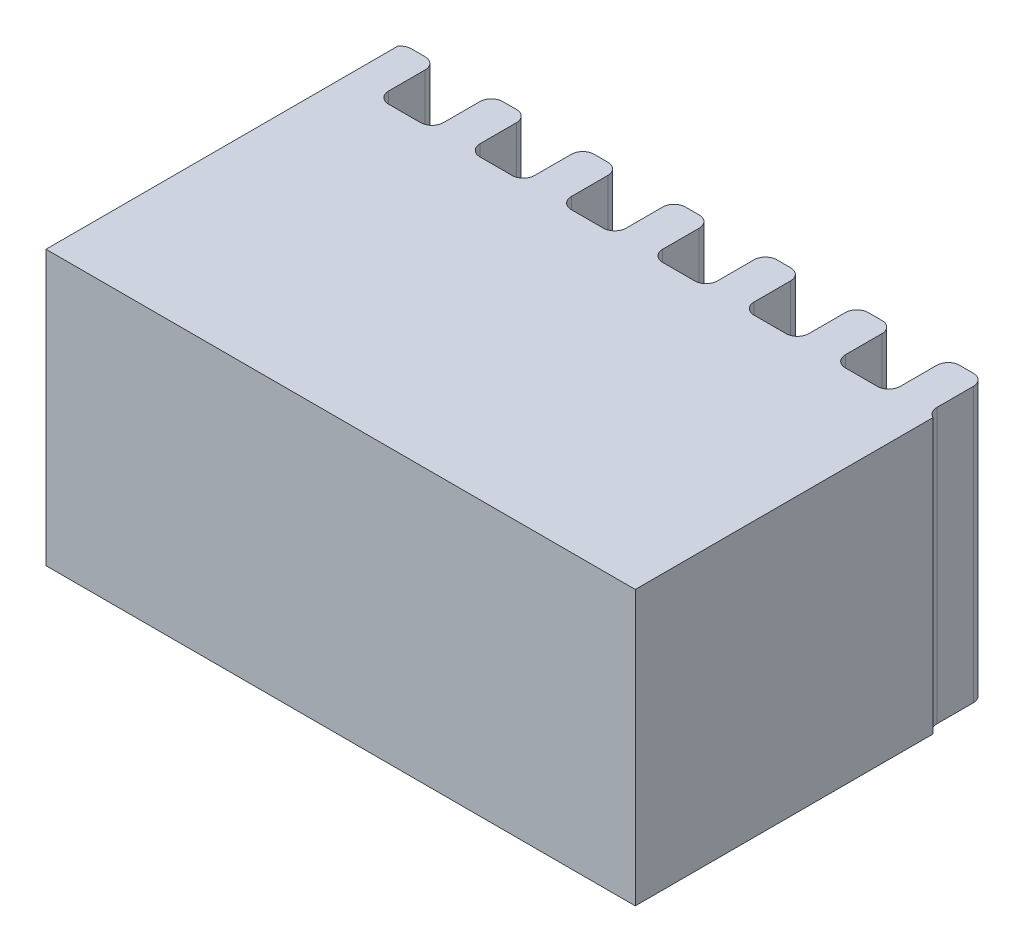
SolidWorks part; units mm, degrees
ref_plane "前视基准面" through (0, 0, 0) normal (0, 0, 1) x (1, 0, 0)
ref_plane "上视基准面" through (0, 0, 0) normal (0, 1, 0) x (1, 0, 0)
ref_plane "右视基准面" through (0, 0, 0) normal (1, 0, 0) x (0, 0, -1)
sketch "草图1" plane through (0, 0, 0) normal (0, 1, 0) x (1, 0, 0)
  line L1 (0, 0) -> (45, 0)
  line L2 (0, 0) -> (0, 26)
  line L3 (0, 26) -> (45, 26)
  line L4 (45, 0) -> (45, 26)
  dimension "D1" = 26
  dimension "D2" = 45
extrude "凸台-拉伸1" add sketch "草图1" along normal blind 10
sketch "草图3" plane through (0, 10, 0) normal (0, 1, 0) x (1, 0, 0)
  line L1 (44.35, 9.3) -> (44.35, 7.2991) construction
  line L3 (43, 8) -> (43.7, 8)
  line L4 (44.75, 8.25) -> (44.75, 9.05)
  line L5 (44.5, 9.3) -> (44.2, 9.3)
  line L6 (45, 0) -> (45, 26) construction
  line L7 (43.95, 8.25) -> (43.95, 9.05)
  line L8 (41, 8) -> (41.7, 8)
  line L9 (41.95, 8.25) -> (41.95, 9.05)
  line L10 (42.5, 9.3) -> (42.2, 9.3)
  line L11 (42.75, 8.25) -> (42.75, 9.05)
  line L12 (39, 8) -> (39.7, 8)
  line L13 (39.95, 8.25) -> (39.95, 9.05)
  line L14 (40.5, 9.3) -> (40.2, 9.3)
  line L15 (40.75, 8.25) -> (40.75, 9.05)
  line L16 (37, 8) -> (37.7, 8)
  line L17 (37.95, 8.25) -> (37.95, 9.05)
  line L18 (38.5, 9.3) -> (38.2, 9.3)
  line L19 (38.75, 8.25) -> (38.75, 9.05)
  line L20 (35, 8) -> (35.7, 8)
  line L21 (35.95, 8.25) -> (35.95, 9.05)
  line L22 (36.5, 9.3) -> (36.2, 9.3)
  line L23 (36.75, 8.25) -> (36.75, 9.05)
  line L24 (33, 8) -> (33.7, 8)
  line L25 (33.95, 8.25) -> (33.95, 9.05)
  line L26 (34.5, 9.3) -> (34.2, 9.3)
  line L27 (34.75, 8.25) -> (34.75, 9.05)
  line L28 (31, 8) -> (31.7, 8)
  line L29 (31.95, 8.25) -> (31.95, 9.05)
  line L30 (32.5, 9.3) -> (32.2, 9.3)
  line L31 (32.75, 8.25) -> (32.75, 9.05)
  line L32 (29, 8) -> (29.7, 8)
  line L33 (29.95, 8.25) -> (29.95, 9.05)
  line L34 (30.5, 9.3) -> (30.2, 9.3)
  line L35 (30.75, 8.25) -> (30.75, 9.05)
  line L36 (27, 8) -> (27.7, 8)
  line L37 (27.95, 8.25) -> (27.95, 9.05)
  line L38 (28.5, 9.3) -> (28.2, 9.3)
  line L39 (28.75, 8.25) -> (28.75, 9.05)
  line L40 (25, 8) -> (25.7, 8)
  line L41 (25.95, 8.25) -> (25.95, 9.05)
  line L42 (26.5, 9.3) -> (26.2, 9.3)
  line L43 (26.75, 8.25) -> (26.75, 9.05)
  line L44 (23, 8) -> (23.7, 8)
  line L45 (23.95, 8.25) -> (23.95, 9.05)
  line L46 (24.5, 9.3) -> (24.2, 9.3)
  line L47 (24.75, 8.25) -> (24.75, 9.05)
  line L48 (21, 8) -> (21.7, 8)
  line L49 (21.95, 8.25) -> (21.95, 9.05)
  line L50 (22.5, 9.3) -> (22.2, 9.3)
  line L51 (22.75, 8.25) -> (22.75, 9.05)
  line L52 (19, 8) -> (19.7, 8)
  line L53 (19.95, 8.25) -> (19.95, 9.05)
  line L54 (20.5, 9.3) -> (20.2, 9.3)
  line L55 (20.75, 8.25) -> (20.75, 9.05)
  line L56 (17, 8) -> (17.7, 8)
  line L57 (17.95, 8.25) -> (17.95, 9.05)
  line L58 (18.5, 9.3) -> (18.2, 9.3)
  line L59 (18.75, 8.25) -> (18.75, 9.05)
  line L60 (15, 8) -> (15.7, 8)
  line L61 (15.95, 8.25) -> (15.95, 9.05)
  line L62 (16.5, 9.3) -> (16.2, 9.3)
  line L63 (16.75, 8.25) -> (16.75, 9.05)
  line L64 (13, 8) -> (13.7, 8)
  line L65 (13.95, 8.25) -> (13.95, 9.05)
  line L66 (14.5, 9.3) -> (14.2, 9.3)
  line L67 (14.75, 8.25) -> (14.75, 9.05)
  line L68 (11, 8) -> (11.7, 8)
  line L69 (11.95, 8.25) -> (11.95, 9.05)
  line L70 (12.5, 9.3) -> (12.2, 9.3)
  line L71 (12.75, 8.25) -> (12.75, 9.05)
  line L72 (9, 8) -> (9.7, 8)
  line L73 (9.95, 8.25) -> (9.95, 9.05)
  line L74 (10.5, 9.3) -> (10.2, 9.3)
  line L75 (10.75, 8.25) -> (10.75, 9.05)
  line L76 (7, 8) -> (7.7, 8)
  line L77 (7.95, 8.25) -> (7.95, 9.05)
  line L78 (8.5, 9.3) -> (8.2, 9.3)
  line L79 (8.75, 8.25) -> (8.75, 9.05)
  line L80 (5, 8) -> (5.7, 8)
  line L81 (5.95, 8.25) -> (5.95, 9.05)
  line L82 (6.5, 9.3) -> (6.2, 9.3)
  line L83 (6.75, 8.25) -> (6.75, 9.05)
  line L84 (3, 8) -> (3.7, 8)
  line L85 (3.95, 8.25) -> (3.95, 9.05)
  line L86 (4.5, 9.3) -> (4.2, 9.3)
  line L87 (4.75, 8.25) -> (4.75, 9.05)
  line L88 (1, 8) -> (1.7, 8)
  line L89 (1.95, 8.25) -> (1.95, 9.05)
  line L90 (2.5, 9.3) -> (2.2, 9.3)
  line L91 (2.75, 8.25) -> (2.75, 9.05)
  line L92 (0, 10.2) -> (0, 9.2)
  line L94 (0.5, 9.3) -> (0.2, 9.3)
  line L95 (0.75, 8.25) -> (0.75, 9.05)
  line L96 (0, 10.2) -> (45, 10.2)
  line L97 (0, 26) -> (0, 0) construction
  line L98 (45, 8) -> (45, 10.2)
  line L101 (-0.05, 8.25) -> (-0.05, 9.05) [skipped]
  line L102 (-1, 8) -> (-0.3, 8) [skipped]
  arc A0 (45, 8) -> (44.75, 8.25) centre (45, 8.25) cw
  arc A1 (44.75, 9.05) -> (44.5, 9.3) centre (44.5, 9.05) ccw
  arc A2 (43.7, 8) -> (43.95, 8.25) centre (43.7, 8.25) ccw
  arc A3 (43.95, 9.05) -> (44.2, 9.3) centre (44.2, 9.05) cw
  arc A4 (41.7, 8) -> (41.95, 8.25) centre (41.7, 8.25) ccw
  arc A5 (41.95, 9.05) -> (42.2, 9.3) centre (42.2, 9.05) cw
  arc A6 (42.75, 9.05) -> (42.5, 9.3) centre (42.5, 9.05) ccw
  arc A7 (43, 8) -> (42.75, 8.25) centre (43, 8.25) cw
  arc A8 (39.7, 8) -> (39.95, 8.25) centre (39.7, 8.25) ccw
  arc A9 (39.95, 9.05) -> (40.2, 9.3) centre (40.2, 9.05) cw
  arc A10 (40.75, 9.05) -> (40.5, 9.3) centre (40.5, 9.05) ccw
  arc A11 (41, 8) -> (40.75, 8.25) centre (41, 8.25) cw
  arc A12 (37.7, 8) -> (37.95, 8.25) centre (37.7, 8.25) ccw
  arc A13 (37.95, 9.05) -> (38.2, 9.3) centre (38.2, 9.05) cw
  arc A14 (38.75, 9.05) -> (38.5, 9.3) centre (38.5, 9.05) ccw
  arc A15 (39, 8) -> (38.75, 8.25) centre (39, 8.25) cw
  arc A16 (35.7, 8) -> (35.95, 8.25) centre (35.7, 8.25) ccw
  arc A17 (35.95, 9.05) -> (36.2, 9.3) centre (36.2, 9.05) cw
  arc A18 (36.75, 9.05) -> (36.5, 9.3) centre (36.5, 9.05) ccw
  arc A19 (37, 8) -> (36.75, 8.25) centre (37, 8.25) cw
  arc A20 (33.7, 8) -> (33.95, 8.25) centre (33.7, 8.25) ccw
  arc A21 (33.95, 9.05) -> (34.2, 9.3) centre (34.2, 9.05) cw
  arc A22 (34.75, 9.05) -> (34.5, 9.3) centre (34.5, 9.05) ccw
  arc A23 (35, 8) -> (34.75, 8.25) centre (35, 8.25) cw
  arc A24 (31.7, 8) -> (31.95, 8.25) centre (31.7, 8.25) ccw
  arc A25 (31.95, 9.05) -> (32.2, 9.3) centre (32.2, 9.05) cw
  arc A26 (32.75, 9.05) -> (32.5, 9.3) centre (32.5, 9.05) ccw
  arc A27 (33, 8) -> (32.75, 8.25) centre (33, 8.25) cw
  arc A28 (29.7, 8) -> (29.95, 8.25) centre (29.7, 8.25) ccw
  arc A29 (29.95, 9.05) -> (30.2, 9.3) centre (30.2, 9.05) cw
  arc A30 (30.75, 9.05) -> (30.5, 9.3) centre (30.5, 9.05) ccw
  arc A31 (31, 8) -> (30.75, 8.25) centre (31, 8.25) cw
  arc A32 (27.7, 8) -> (27.95, 8.25) centre (27.7, 8.25) ccw
  arc A33 (27.95, 9.05) -> (28.2, 9.3) centre (28.2, 9.05) cw
  arc A34 (28.75, 9.05) -> (28.5, 9.3) centre (28.5, 9.05) ccw
  arc A35 (29, 8) -> (28.75, 8.25) centre (29, 8.25) cw
  arc A36 (25.7, 8) -> (25.95, 8.25) centre (25.7, 8.25) ccw
  arc A37 (25.95, 9.05) -> (26.2, 9.3) centre (26.2, 9.05) cw
  arc A38 (26.75, 9.05) -> (26.5, 9.3) centre (26.5, 9.05) ccw
  arc A39 (27, 8) -> (26.75, 8.25) centre (27, 8.25) cw
  arc A40 (23.7, 8) -> (23.95, 8.25) centre (23.7, 8.25) ccw
  arc A41 (23.95, 9.05) -> (24.2, 9.3) centre (24.2, 9.05) cw
  arc A42 (24.75, 9.05) -> (24.5, 9.3) centre (24.5, 9.05) ccw
  arc A43 (25, 8) -> (24.75, 8.25) centre (25, 8.25) cw
  arc A44 (21.7, 8) -> (21.95, 8.25) centre (21.7, 8.25) ccw
  arc A45 (21.95, 9.05) -> (22.2, 9.3) centre (22.2, 9.05) cw
  arc A46 (22.75, 9.05) -> (22.5, 9.3) centre (22.5, 9.05) ccw
  arc A47 (23, 8) -> (22.75, 8.25) centre (23, 8.25) cw
  arc A48 (19.7, 8) -> (19.95, 8.25) centre (19.7, 8.25) ccw
  arc A49 (19.95, 9.05) -> (20.2, 9.3) centre (20.2, 9.05) cw
  arc A50 (20.75, 9.05) -> (20.5, 9.3) centre (20.5, 9.05) ccw
  arc A51 (21, 8) -> (20.75, 8.25) centre (21, 8.25) cw
  arc A52 (17.7, 8) -> (17.95, 8.25) centre (17.7, 8.25) ccw
  arc A53 (17.95, 9.05) -> (18.2, 9.3) centre (18.2, 9.05) cw
  arc A54 (18.75, 9.05) -> (18.5, 9.3) centre (18.5, 9.05) ccw
  arc A55 (19, 8) -> (18.75, 8.25) centre (19, 8.25) cw
  arc A56 (15.7, 8) -> (15.95, 8.25) centre (15.7, 8.25) ccw
  arc A57 (15.95, 9.05) -> (16.2, 9.3) centre (16.2, 9.05) cw
  arc A58 (16.75, 9.05) -> (16.5, 9.3) centre (16.5, 9.05) ccw
  arc A59 (17, 8) -> (16.75, 8.25) centre (17, 8.25) cw
  arc A60 (13.7, 8) -> (13.95, 8.25) centre (13.7, 8.25) ccw
  arc A61 (13.95, 9.05) -> (14.2, 9.3) centre (14.2, 9.05) cw
  arc A62 (14.75, 9.05) -> (14.5, 9.3) centre (14.5, 9.05) ccw
  arc A63 (15, 8) -> (14.75, 8.25) centre (15, 8.25) cw
  arc A64 (11.7, 8) -> (11.95, 8.25) centre (11.7, 8.25) ccw
  arc A65 (11.95, 9.05) -> (12.2, 9.3) centre (12.2, 9.05) cw
  arc A66 (12.75, 9.05) -> (12.5, 9.3) centre (12.5, 9.05) ccw
  arc A67 (13, 8) -> (12.75, 8.25) centre (13, 8.25) cw
  arc A68 (9.7, 8) -> (9.95, 8.25) centre (9.7, 8.25) ccw
  arc A69 (9.95, 9.05) -> (10.2, 9.3) centre (10.2, 9.05) cw
  arc A70 (10.75, 9.05) -> (10.5, 9.3) centre (10.5, 9.05) ccw
  arc A71 (11, 8) -> (10.75, 8.25) centre (11, 8.25) cw
  arc A72 (7.7, 8) -> (7.95, 8.25) centre (7.7, 8.25) ccw
  arc A73 (7.95, 9.05) -> (8.2, 9.3) centre (8.2, 9.05) cw
  arc A74 (8.75, 9.05) -> (8.5, 9.3) centre (8.5, 9.05) ccw
  arc A75 (9, 8) -> (8.75, 8.25) centre (9, 8.25) cw
  arc A76 (5.7, 8) -> (5.95, 8.25) centre (5.7, 8.25) ccw
  arc A77 (5.95, 9.05) -> (6.2, 9.3) centre (6.2, 9.05) cw
  arc A78 (6.75, 9.05) -> (6.5, 9.3) centre (6.5, 9.05) ccw
  arc A79 (7, 8) -> (6.75, 8.25) centre (7, 8.25) cw
  arc A80 (3.7, 8) -> (3.95, 8.25) centre (3.7, 8.25) ccw
  arc A81 (3.95, 9.05) -> (4.2, 9.3) centre (4.2, 9.05) cw
  arc A82 (4.75, 9.05) -> (4.5, 9.3) centre (4.5, 9.05) ccw
  arc A83 (5, 8) -> (4.75, 8.25) centre (5, 8.25) cw
  arc A84 (1.7, 8) -> (1.95, 8.25) centre (1.7, 8.25) ccw
  arc A85 (1.95, 9.05) -> (2.2, 9.3) centre (2.2, 9.05) cw
  arc A86 (2.75, 9.05) -> (2.5, 9.3) centre (2.5, 9.05) ccw
  arc A87 (3, 8) -> (2.75, 8.25) centre (3, 8.25) cw
  arc A89 (0, 9.2) -> (0.2, 9.3) centre (0.2, 9.05) cw
  arc A90 (0.75, 9.05) -> (0.5, 9.3) centre (0.5, 9.05) ccw
  arc A91 (1, 8) -> (0.75, 8.25) centre (1, 8.25) cw
  arc A92 (-0.3, 8) -> (-0.05, 8.25) centre (-0.3, 8.25) ccw [skipped]
  dimension "D2" = 2
  dimension "D4" = 0.25
  dimension "D5" = 0.25
  dimension "D1" = 0
  dimension "D3" = 23
  dimension "D6" = 0.8
  dimension "D7" = 0.9
extrude "切除-拉伸1" cut sketch "草图3" against normal blind 6
sketch "草图4" plane through (0, 10, 0) normal (0, 1, 0) x (1, 0, 0)
  line L1 (45, 8) -> (15, 8)
  line L2 (45, 8) -> (45, 9.4)
  line L3 (45, 9.4) -> (15, 9.4)
  line L4 (15, 8) -> (15, 9.4)
  dimension "D1" = 1.4
  dimension "D2" = 30
extrude "切除-拉伸3" cut sketch "草图4" against normal blind 6
sketch "草图5" plane through (45, 0, 0) normal (1, 0, 0) x (0, 0, -1)
  line L0 (8, 7) -> (0, 7) construction
  line L1 (8, 4) -> (8, 10) construction
  line L2 (0, 10) -> (0, 0) construction
  line L3 (4.5, 10) -> (4.5, 0) construction
  line L4 (0, 10) -> (8, 10) construction
  line L5 (0, 0) -> (26, 0) construction
  circle A0 centre (4.5, 7) radius 1.8
  dimension "D3" = 3.6
  dimension "D1" = 3
  dimension "D2" = 3.5
extrude "切除-拉伸4" cut sketch "草图5" against normal blind 30
sketch "草图6" plane through (0, 10, 0) normal (0, 1, 0) x (1, 0, 0)
  line L0 (45, 4.5) -> (25.0035, 4.5) construction
  line L1 (45, 0) -> (45, 8) construction
  line L2 (15, 8) -> (45, 8) construction
  line L4 (37.2, 7.5) -> (40, 7.5)
  line L5 (37.2, 7.5) -> (37.2, 1.5)
  line L6 (37.2, 1.5) -> (40, 1.5)
  line L7 (40, 7.5) -> (40, 1.5)
  dimension "D1" = 3.5
  dimension "D2" = 5
  dimension "D3" = 2.8
  dimension "D4" = 6
  dimension "D5" = 3
extrude "切除-拉伸5" cut sketch "草图6" against normal blind 6.5
sketch "草图7" plane through (0, 10, 0) normal (0, 1, 0) x (1, 0, 0)
  line L0 (37.2, 7.5) -> (37.2, 1.5) construction
  line L1 (35.2, 1.5) -> (12.9, 1.5)
  line L2 (35.2, 1.5) -> (35.2, 9.613)
  line L3 (35.2, 9.613) -> (12.9, 9.613)
  line L4 (12.9, 1.5) -> (12.9, 9.613)
  line L5 (0, 0) -> (45, 0) construction
  dimension "D1" = 2
  dimension "D2" = 22.3
  dimension "D3" = 1.5
extrude "切除-拉伸7" cut sketch "草图7" against normal blind 6
sketch "草图8" plane through (0, 0, -26) normal (0, 0, -1) x (-1, 0, 0)
  line L0 (0, 5) -> (-45, 5) construction
  line L1 (0, 10) -> (0, 0) construction
  line L2 (-45, 10) -> (-45, 0) construction
  line L3 (-22.5, 0) -> (-22.5, 10) construction
  line L4 (-45, 0) -> (0, 0) construction
  line L5 (-45, 10) -> (0, 10) construction
  circle A0 centre (-10, 5) radius 1.9
  circle A1 centre (-35, 5) radius 1.9
  dimension "D1" = 3.8
  dimension "D2" = 12.5
extrude "切除-拉伸8" cut sketch "草图8" against normal blind 15.9
sketch "草图9" plane through (0, 10, 0) normal (0, 1, 0) x (1, 0, 0)
  line L0 (22.5, 26) -> (22.5, 10.2) construction
  line L1 (45, 26) -> (0, 26) construction
  line L2 (45, 10.2) -> (0, 10.2) construction
sketch "草图10" plane through (0, 10, 0) normal (0, 1, 0) x (1, 0, 0)
  line L0 (22.5, 26) -> (22.5, 10.2) construction
  line L1 (7, 23) -> (13, 23)
  line L2 (7, 23) -> (7, 20)
  line L3 (7, 20) -> (13, 20)
  line L4 (13, 23) -> (13, 20)
  line L7 (22.5, 26) -> (22.5, 10.2) construction
  line L8 (38, 23) -> (38, 20)
  line L9 (38, 20) -> (32, 20)
  line L10 (32, 23) -> (32, 20)
  line L11 (38, 23) -> (32, 23)
  line L12 (45, 26) -> (0, 26) construction
  dimension "D1" = 6
  dimension "D2" = 3
  dimension "D3" = 9.5
  dimension "D4" = 3
extrude "切除-拉伸9" cut sketch "草图10" against normal blind 8.5
sketch "草图12" plane through (0, 0, 0) normal (-1, 0, 0) x (0, 0, 1)
  line L1 (0, 0) -> (-10.2, 0)
  line L2 (0, 0) -> (0, 4)
  line L3 (0, 4) -> (-10.2, 4)
  line L4 (-10.2, 0) -> (-10.2, 4)
extrude "切除-拉伸11" cut sketch "草图12" against normal blind 45
sketch "草图13" plane through (0, 10, 0) normal (0, 1, 0) x (1, 0, 0)
  line L1 (12.9, 1.5) -> (0, 1.5)
  line L2 (12.9, 1.5) -> (12.9, 0)
  line L3 (12.9, 0) -> (0, 0)
  line L4 (0, 1.5) -> (0, 0)
extrude "切除-拉伸12" cut sketch "草图13" against normal blind 6
sketch "草图14" plane through (0, 0, 0) normal (-1, 0, 0) x (0, 0, 1)
  line L0 (-9.2, 7) -> (-1.5, 7) construction
  line L1 (-9.2, 4) -> (-9.2, 10) construction
  line L2 (-1.5, 4) -> (-1.5, 10) construction
  line L3 (-4.5, 4) -> (-4.5, 10) construction
  line L4 (-1.5, 4) -> (-9.2, 4) construction
  line L5 (-9.2, 10) -> (-1.5, 10) construction
  circle A0 centre (-4.5, 7) radius 1.8
  dimension "D2" = 3.6
  dimension "D1" = 3
extrude "切除-拉伸13" cut sketch "草图14" against normal blind 6
